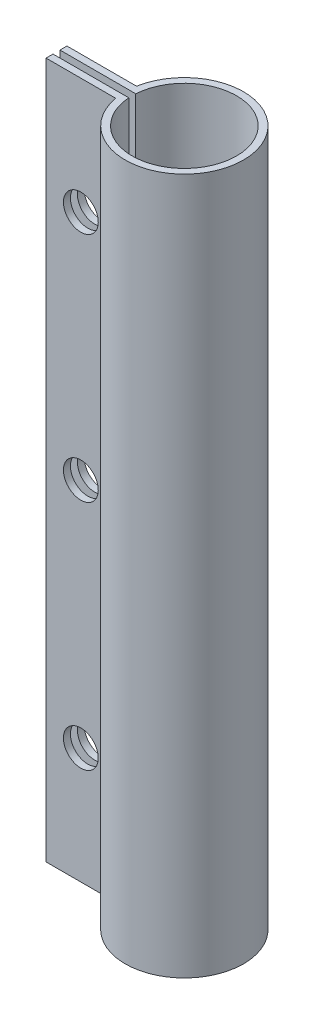
SolidWorks part; units mm, degrees
material "Kupfer"
ref_plane "Ebene vorne" through (0, 0, 0) normal (0, 0, 1) x (1, 0, 0)
ref_plane "Ebene oben" through (0, 0, 0) normal (0, 1, 0) x (1, 0, 0)
ref_plane "Ebene rechts" through (0, 0, 0) normal (1, 0, 0) x (0, 0, -1)
sketch "Skizze1" plane through (0, 0, 0) normal (0, 1, 0) x (1, 0, 0)
  line L0 (0, 0) -> (-3.9625, 0) construction
  line L1 (-9.1833, 0.25) -> (-9.1833, -0.25) construction
  line L2 (-4.1833, 0.25) -> (-3.7417, 0.25)
  line L3 (-4.1833, 0.25) -> (-4.1833, -0.25) construction
  line L4 (-4.1833, -0.25) -> (-3.7417, -0.25)
  line L5 (-3.7417, 0.25) -> (-3.7417, -0.25) construction
  line L6 (-4.1833, 0.25) -> (-3.7417, -0.25) construction
  line L7 (-4.1833, -0.25) -> (-3.7417, 0.25) construction
  line L8 (-4.1833, 0.25) -> (-9.1833, 0.25)
  line L9 (-4.1833, 0.25) -> (-4.1833, 0.75) construction
  line L10 (-4.1833, 0.75) -> (-9.1833, 0.75)
  line L11 (-9.1833, 0.25) -> (-9.1833, 0.75)
  line L12 (-4.1833, 0.25) -> (-9.1833, 0.75) construction
  line L13 (-4.1833, 0.75) -> (-9.1833, 0.25) construction
  line L14 (-4.1833, -0.25) -> (-9.1833, -0.25)
  line L15 (-4.1833, -0.25) -> (-4.1833, -0.75) construction
  line L16 (-4.1833, -0.75) -> (-9.1833, -0.75)
  line L17 (-9.1833, -0.25) -> (-9.1833, -0.75)
  line L18 (-4.1833, -0.25) -> (-9.1833, -0.75) construction
  line L19 (-4.1833, -0.75) -> (-9.1833, -0.25) construction
  arc A0 (-3.7417, 0.25) -> (-3.7417, -0.25) centre (0, 0) cw
  arc A1 (-4.1833, 0.75) -> (-4.1833, -0.75) centre (0, 0) cw
  point P10 (-6.6833, 0.5)
  point P14 (-6.6833, -0.5)
  dimension "D1" = 0.5
  dimension "D2" = 7.5
  dimension "D3" = 0.5
  dimension "D4" = 0.5
  dimension "D5" = 5
extrude "Aufsatz-Linear austragen1" add sketch "Skizze1" along normal blind 50
sketch "Skizze2" plane through (0, 0, 0.75) normal (0, 0, 1) x (1, 0, 0)
  line L0 (-6.6833, 50) -> (-6.6833, 33.3333) construction
  line L2 (-9.1833, 50) -> (-4.1833, 50) construction
  line L3 (-6.6833, 33.3333) -> (-6.6833, 16.6667) construction
  line L4 (-6.6833, 16.6667) -> (-6.6833, 0) construction
  line L6 (-9.1833, 0) -> (-4.1833, 0) construction
  circle A0 centre (-6.6833, 41.6667) radius 1.25
  circle A1 centre (-6.6833, 25) radius 1.25
  circle A2 centre (-6.6833, 8.3333) radius 1.25
  dimension "D1" = 2.5
extrude "Schnitt-Linear austragen1" cut sketch "Skizze2" against normal through all
